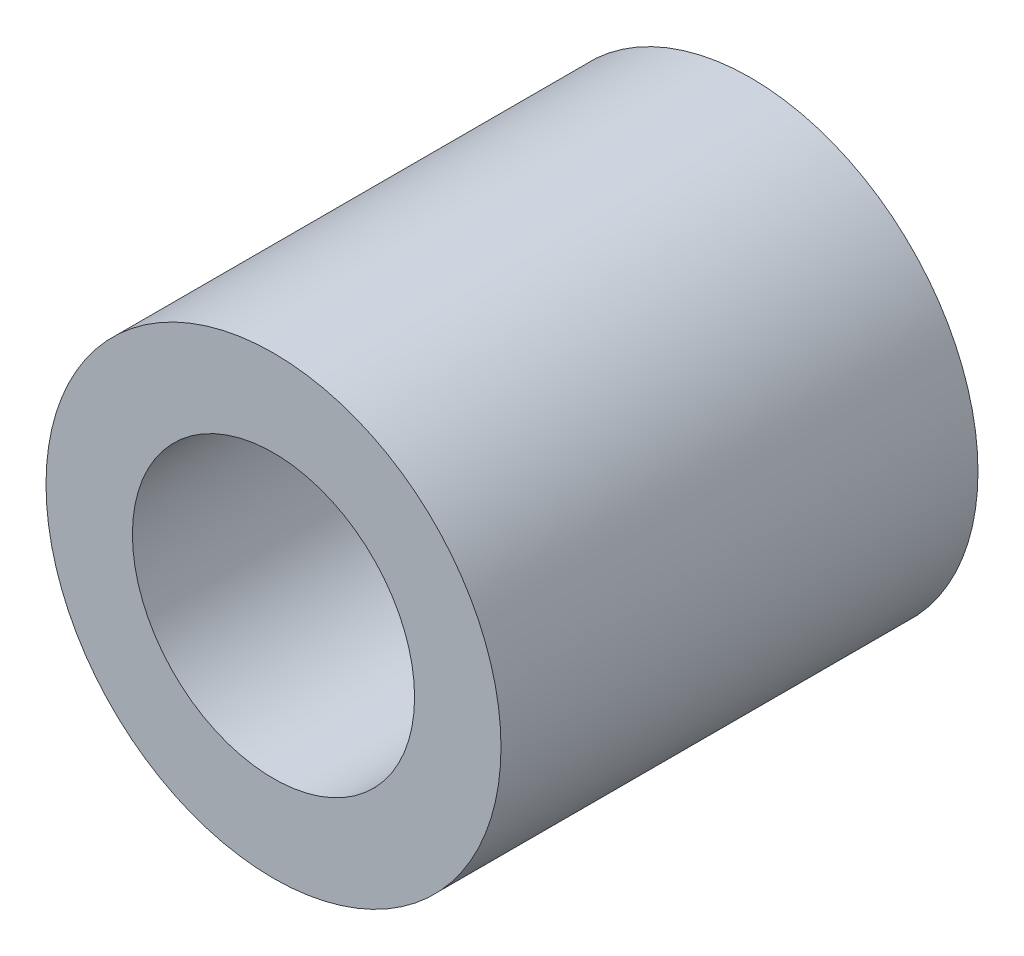
SolidWorks part; units mm, degrees
ref_plane "Front Plane" through (0, 0, 0) normal (0, 0, 1) x (1, 0, 0)
ref_plane "Top Plane" through (0, 0, 0) normal (0, 1, 0) x (1, 0, 0)
ref_plane "Right Plane" through (0, 0, 0) normal (1, 0, 0) x (0, 0, -1)
sketch "Sketch1" plane through (0, 0, 0) normal (0, 0, 1) x (1, 0, 0)
  circle A0 centre (0, 0) radius 47.6917
  circle A1 centre (0, 0) radius 29.5784
  dimension "D1" = 59.1567
  dimension "D2" = 95.3833
extrude "Boss-Extrude1" add sketch "Sketch1" along normal blind 100 contours A1 | A0
